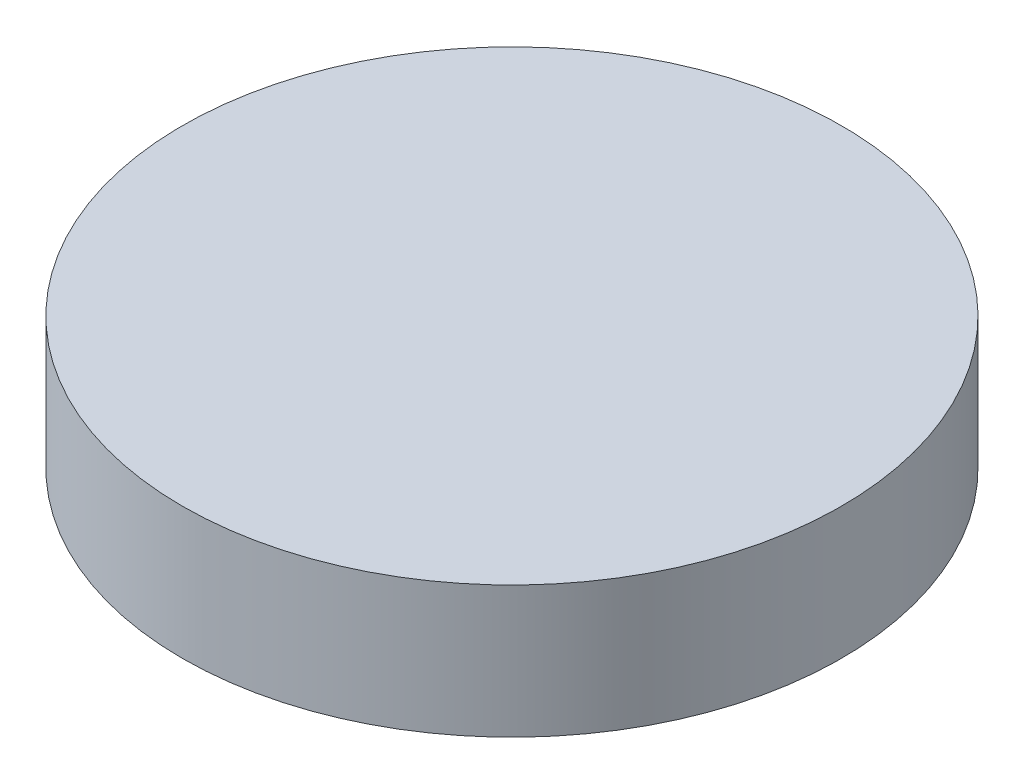
SolidWorks part; units mm, degrees
ref_plane "Front Plane" through (0, 0, 0) normal (0, 0, 1) x (1, 0, 0)
ref_plane "Top Plane" through (0, 0, 0) normal (0, 1, 0) x (1, 0, 0)
ref_plane "Right Plane" through (0, 0, 0) normal (1, 0, 0) x (0, 0, -1)
sketch "Sketch1" plane through (0, 0, 0) normal (0, 1, 0) x (1, 0, 0)
  circle A0 centre (0, 0) radius 31.75
  dimension "D1" = 63.5
extrude "Boss-Extrude1" add sketch "Sketch1" along normal blind 12.7
